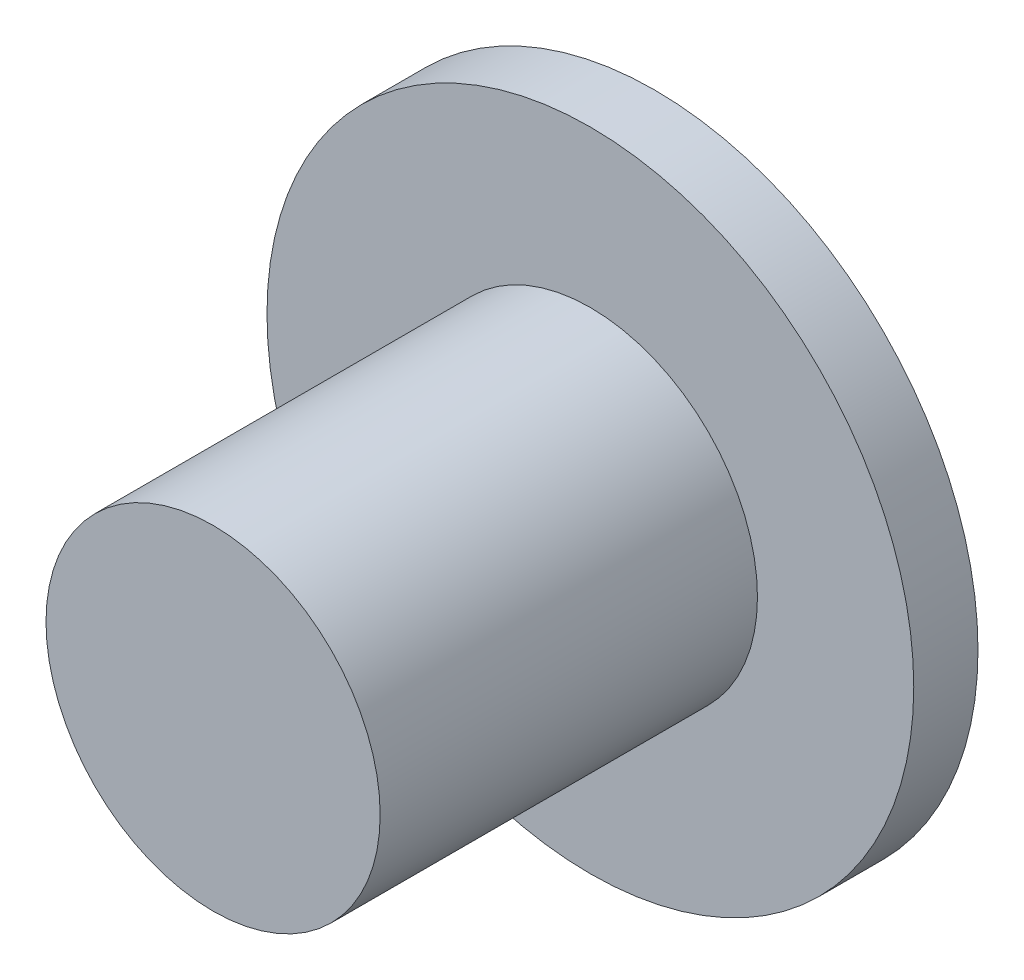
SolidWorks part; units mm, degrees
ref_plane "Front Plane" through (0, 0, 0) normal (0, 0, 1) x (1, 0, 0)
ref_plane "Top Plane" through (0, 0, 0) normal (0, 1, 0) x (1, 0, 0)
ref_plane "Right Plane" through (0, 0, 0) normal (1, 0, 0) x (0, 0, -1)
sketch "Sketch1" plane through (0, 0, 0) normal (0, 0, 1) x (1, 0, 0)
  circle A0 centre (0, 0) radius 3
  dimension "D1" = 6
extrude "Boss-Extrude1" add sketch "Sketch1" along normal blind 1
sketch "Sketch2" plane through (0, 0, 1) normal (0, 0, 1) x (1, 0, 0)
  circle A0 centre (0, 0) radius 1.55
  dimension "D1" = 3.1
extrude "Boss-Extrude2" add sketch "Sketch2" along normal blind 3.5
chamfer "Chamfer1" distance 0.7 angle 30 1 edges at (3, 0, 0)
sketch "Sketch3" plane through (0, 0, 0) normal (0, 0, -1) x (-1, 0, 0)
  circle A0 centre (0, 0) radius 1.15
  dimension "D1" = 2.3
extrude "Cut-Extrude1" cut sketch "Sketch3" against normal blind 0.2
sketch "Sketch4" plane through (0, 0, 0.2) normal (0, 0, -1) x (-1, 0, 0)
  circle A0 centre (0, 0) radius 0.85
  dimension "D1" = 1.7
extrude "Boss-Extrude3" add sketch "Sketch4" along normal blind 0.2
